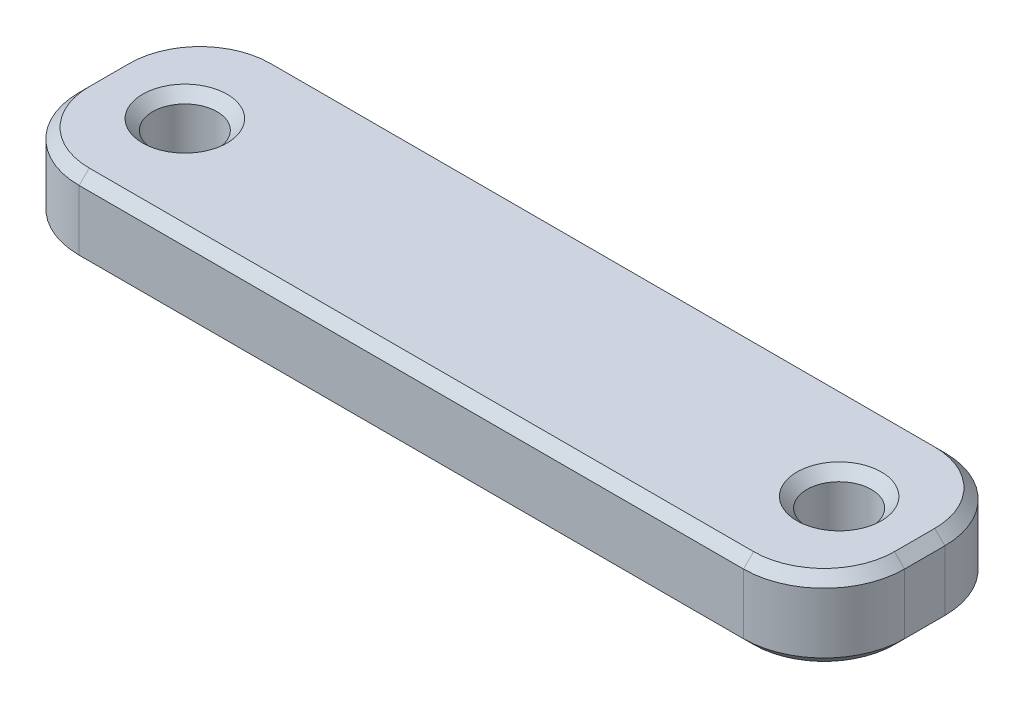
SolidWorks part; units mm, degrees
ref_plane "Front Plane" through (0, 0, 0) normal (0, 0, 1) x (1, 0, 0)
ref_plane "Top Plane" through (0, 0, 0) normal (0, 1, 0) x (1, 0, 0)
ref_plane "Right Plane" through (0, 0, 0) normal (1, 0, 0) x (0, 0, -1)
sketch "Sketch1" plane through (0, 0, 0) normal (0, 1, 0) x (1, 0, 0)
  line L0 (-16.25, 0) -> (16.25, 0) construction
  line L1 (-20.5, 5) -> (20.5, 5)
  line L2 (-20.5, 5) -> (-20.5, -5)
  line L3 (-20.5, -5) -> (20.5, -5)
  line L4 (20.5, 5) -> (20.5, -5)
  line L5 (-20.5, 5) -> (20.5, -5) construction
  line L6 (-20.5, -5) -> (20.5, 5) construction
  circle A0 centre (-16.25, 0) radius 1.6
  circle A1 centre (16.25, 0) radius 1.6
  point P0 (0, 0)
  dimension "D3" = 3.2
  dimension "D1" = 41
  dimension "D2" = 10
  dimension "D4" = 32.5
extrude "Boss-Extrude1" add sketch "Sketch1" along normal blind 4
fillet "Fillet1" radius 4 4 edges at (20.5, 2, -5) (20.5, 2, 5) (-20.5, 2, 5) (-20.5, 2, -5)
chamfer "Chamfer1" distance 0.5 angle 45 20 edges at (16.25, 0, 1.6) (-16.25, 0, 1.6) (0, 0, -5) (-20.5, 0, 0) (0, 0, 5) (20.5, 0, 0) (16.25, 4, 1.6) (0, 4, 5) (-20.5, 4, 0) (0, 4, -5) (20.5, 4, 0) (-16.25, 4, 1.6) (-19.3284, 0, -3.8284) (-19.3284, 0, 3.8284) (19.3284, 0, 3.8284) (19.3284, 0, -3.8284) (19.3284, 4, 3.8284) (-19.3284, 4, 3.8284) (-19.3284, 4, -3.8284) (19.3284, 4, -3.8284)
